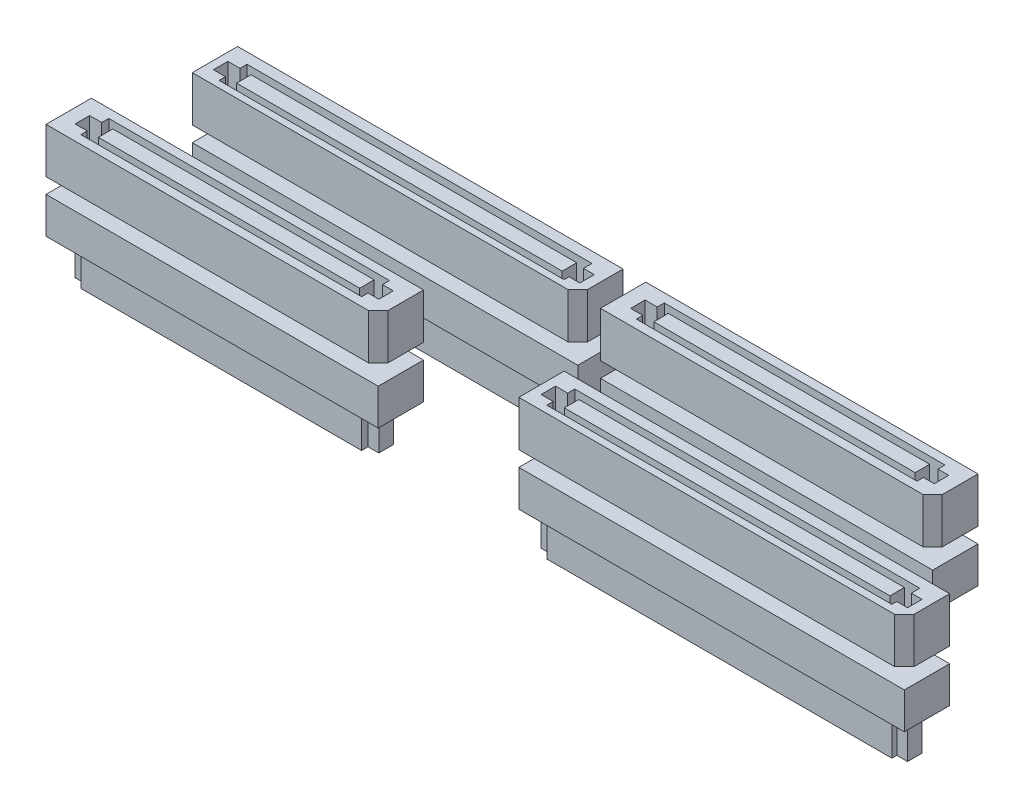
SolidWorks part; units mm, degrees
ref_plane "Front Plane" through (0, 0, 0) normal (0, 0, 1) x (1, 0, 0)
ref_plane "Top Plane" through (0, 0, 0) normal (0, 1, 0) x (1, 0, 0)
ref_plane "Right Plane" through (0, 0, 0) normal (1, 0, 0) x (0, 0, -1)
ref_plane "Plane1" through (0, -1.6866, 0) normal (0, 1, 0) x (1, 0, 0)
ref_plane "center-of-slot" through (0, -0.8433, 0) normal (0, 1, 0) x (1, 0, 0)
sketch "Sketch1" plane through (0, 0, 0) normal (0, 1, 0) x (1, 0, 0)
  line L0 (55.811, 9.5) -> (97.25, 9.5)
  line L1 (3.686, 9.5) -> (39.25, 9.5)
  line L2 (2.625, 8.439) -> (2.625, 4.5)
  line L3 (2.625, 4.5) -> (39.25, 4.5) construction
  line L4 (39.25, 9.5) -> (39.25, 4.5) construction
  line L5 (0, 0) -> (100, 0) construction
  line L6 (0, 0) -> (0, 75) construction
  line L7 (0, 75) -> (100, 75) construction
  line L8 (100, 0) -> (100, 75) construction
  line L9 (54.75, 8.439) -> (54.75, 4.5)
  line L10 (54.75, 4.5) -> (97.25, 4.5) construction
  line L11 (97.25, 9.5) -> (97.25, 4.5) construction
  line L12 (51.811, 22.5) -> (87.375, 22.5)
  line L13 (6.811, 22.5) -> (48.25, 22.5)
  line L14 (5.75, 21.439) -> (5.75, 17.5)
  line L15 (5.75, 17.5) -> (48.25, 17.5) construction
  line L16 (48.25, 22.5) -> (48.25, 17.5) construction
  line L17 (50.75, 21.439) -> (50.75, 17.5)
  line L18 (50.75, 17.5) -> (87.375, 17.5) construction
  line L19 (87.375, 22.5) -> (87.375, 17.5) construction
  line L20 (5.75, 21.439) -> (6.811, 22.5) construction
  line L21 (50.75, 21.439) -> (51.811, 22.5) construction
  line L22 (54.75, 8.439) -> (55.811, 9.5) construction
  line L23 (2.625, 8.439) -> (3.686, 9.5) construction
  line L24 (2.625, 4.5) -> (38.195, 4.5)
  line L25 (38.195, 4.5) -> (39.25, 5.555)
  line L26 (39.25, 5.555) -> (39.25, 9.5)
  line L27 (50.75, 17.5) -> (86.32, 17.5)
  line L28 (86.32, 17.5) -> (87.375, 18.555)
  line L29 (87.375, 18.555) -> (87.375, 22.5)
  line L30 (54.75, 4.5) -> (96.19, 4.5)
  line L31 (96.19, 4.5) -> (97.25, 5.56)
  line L32 (97.25, 5.56) -> (97.25, 9.5)
  line L33 (5.75, 17.5) -> (47.19, 17.5)
  line L34 (47.19, 17.5) -> (48.25, 18.56)
  line L35 (48.25, 18.56) -> (48.25, 22.5)
  line L36 (5.75, 21.439) -> (5.75, 22.5)
  line L37 (5.75, 22.5) -> (6.811, 22.5)
  line L38 (2.625, 8.439) -> (2.625, 9.5)
  line L39 (2.625, 9.5) -> (3.686, 9.5)
  line L40 (54.75, 8.439) -> (54.75, 9.5)
  line L41 (54.75, 9.5) -> (55.811, 9.5)
  line L42 (50.75, 21.439) -> (50.75, 22.5)
  line L43 (50.75, 22.5) -> (51.811, 22.5)
  point P0 (2.625, 9.5)
  point P9 (54.75, 9.5)
  point P13 (5.75, 22.5)
  point P17 (50.75, 22.5)
extrude "SV" add sketch "Sketch1" along normal blind 5
sketch "Sketch3" plane through (0, 5, 0) normal (0, 1, 0) x (1, 0, 0)
  line L0 (4.1893, 7.7457) -> (5.5243, 7.7457)
  line L1 (4.1893, 8.5242) -> (37.667, 8.5242) construction
  line L2 (4.1893, 8.5242) -> (4.1893, 5.4386) construction
  line L3 (4.1893, 5.4386) -> (37.667, 5.4386) construction
  line L4 (37.667, 8.5242) -> (37.667, 5.4386) construction
  line L5 (5.5243, 7.7457) -> (5.5243, 8.5242)
  line L6 (5.5243, 8.5242) -> (36.4757, 8.5242)
  line L7 (36.4757, 8.5242) -> (36.4757, 7.7457)
  line L8 (36.4757, 7.7457) -> (37.667, 7.7457)
  line L9 (37.667, 7.7457) -> (37.667, 6.1479)
  line L10 (37.667, 6.1479) -> (36.4757, 6.1479)
  line L11 (36.4757, 6.1479) -> (36.4757, 5.4386)
  line L12 (36.4757, 5.4386) -> (5.5243, 5.4386)
  line L13 (5.5243, 5.4386) -> (5.5243, 6.1479)
  line L14 (5.5243, 6.1479) -> (4.1893, 6.1479)
  line L15 (4.1893, 6.1479) -> (4.1893, 7.7457)
  line L16 (52.4211, 20.7536) -> (53.7561, 20.7536)
  line L17 (6.7471, 7.7457) -> (35.5588, 7.7457)
  line L18 (6.7471, 7.7457) -> (6.7471, 6.1479)
  line L19 (6.7471, 6.1479) -> (35.5588, 6.1479)
  line L20 (35.5588, 7.7457) -> (35.5588, 6.1479)
  line L21 (52.4211, 21.532) -> (85.8988, 21.532) construction
  line L22 (52.4211, 21.532) -> (52.4211, 18.4464) construction
  line L23 (52.4211, 18.4464) -> (85.8988, 18.4464) construction
  line L24 (85.8988, 21.532) -> (85.8988, 18.4464) construction
  line L25 (53.7561, 20.7536) -> (53.7561, 21.532)
  line L26 (53.7561, 21.532) -> (84.7075, 21.532)
  line L27 (84.7075, 21.532) -> (84.7075, 20.7536)
  line L28 (84.7075, 20.7536) -> (85.8988, 20.7536)
  line L29 (85.8988, 20.7536) -> (85.8988, 19.1558)
  line L30 (85.8988, 19.1558) -> (84.7075, 19.1558)
  line L31 (84.7075, 19.1558) -> (84.7075, 18.4464)
  line L32 (84.7075, 18.4464) -> (53.7561, 18.4464)
  line L33 (53.7561, 18.4464) -> (53.7561, 19.1558)
  line L34 (53.7561, 19.1558) -> (52.4211, 19.1558)
  line L35 (52.4211, 19.1558) -> (52.4211, 20.7536)
  line L36 (54.9789, 20.7536) -> (83.7906, 20.7536)
  line L37 (54.9789, 20.7536) -> (54.9789, 19.1558)
  line L38 (54.9789, 19.1558) -> (83.7906, 19.1558)
  line L39 (83.7906, 20.7536) -> (83.7906, 19.1558)
  line L40 (55.7059, 7.599) -> (57.0409, 7.599)
  line L41 (55.7059, 8.3775) -> (96.2696, 8.3775) construction
  line L42 (55.7059, 8.3775) -> (55.7059, 5.2919) construction
  line L43 (55.7059, 5.2919) -> (96.2696, 5.2919) construction
  line L44 (96.2696, 8.3775) -> (96.2696, 5.2919) construction
  line L45 (57.0409, 7.599) -> (57.0409, 8.3775)
  line L46 (57.0409, 8.3775) -> (95.0783, 8.3775)
  line L47 (95.0783, 8.3775) -> (95.0783, 7.4377)
  line L48 (95.0783, 7.4377) -> (96.2696, 7.4377)
  line L49 (96.2696, 7.4377) -> (96.2696, 5.8399)
  line L50 (96.2696, 5.8399) -> (95.0783, 5.8399)
  line L51 (95.0783, 5.8399) -> (95.0783, 5.2919)
  line L52 (95.0783, 5.2919) -> (57.0409, 5.2919)
  line L53 (57.0409, 5.2919) -> (57.0409, 6.0012)
  line L54 (57.0409, 6.0012) -> (55.7059, 6.0012)
  line L55 (55.7059, 6.0012) -> (55.7059, 7.599)
  line L56 (58.2637, 7.599) -> (94.1615, 7.599)
  line L57 (58.2637, 7.599) -> (58.2637, 6.0012)
  line L58 (58.2637, 6.0012) -> (94.1615, 6.0012)
  line L59 (94.1615, 7.599) -> (94.1615, 6.0012)
  line L60 (6.6366, 20.5397) -> (7.9716, 20.5397)
  line L61 (6.6366, 21.3182) -> (47.2003, 21.3182) construction
  line L62 (6.6366, 21.3182) -> (6.6366, 18.2325) construction
  line L63 (6.6366, 18.2325) -> (47.2003, 18.2325) construction
  line L64 (47.2003, 21.3182) -> (47.2003, 18.2325) construction
  line L65 (7.9716, 20.5397) -> (7.9716, 21.3182)
  line L66 (7.9716, 21.3182) -> (46.009, 21.3182)
  line L67 (46.009, 21.3182) -> (46.009, 20.3784)
  line L68 (46.009, 20.3784) -> (47.2003, 20.3784)
  line L69 (47.2003, 20.3784) -> (47.2003, 18.7806)
  line L70 (47.2003, 18.7806) -> (46.009, 18.7806)
  line L71 (46.009, 18.7806) -> (46.009, 18.2325)
  line L72 (46.009, 18.2325) -> (7.9716, 18.2325)
  line L73 (7.9716, 18.2325) -> (7.9716, 18.9419)
  line L74 (7.9716, 18.9419) -> (6.6366, 18.9419)
  line L75 (6.6366, 18.9419) -> (6.6366, 20.5397)
  line L76 (9.1944, 20.5397) -> (45.0922, 20.5397)
  line L77 (9.1944, 20.5397) -> (9.1944, 18.9419)
  line L78 (9.1944, 18.9419) -> (45.0922, 18.9419)
  line L79 (45.0922, 20.5397) -> (45.0922, 18.9419)
extrude "Cut-Extrude1" cut sketch "Sketch3" against normal blind 4
sketch "Sketch6" plane through (0, -1.6866, 0) normal (0, 1, 0) x (1, 0, 0)
  line L0 (2.625, 4.5) -> (2.625, 9.5) construction
  line L1 (5.75, 22.5) -> (48.25, 22.5) construction
  line L2 (5.75, 22.5) -> (5.75, 17.5) construction
  line L3 (5.75, 17.5) -> (48.25, 17.5) construction
  line L4 (48.25, 22.5) -> (48.25, 17.5) construction
  line L5 (50.75, 22.5) -> (87.375, 22.5) construction
  line L6 (50.75, 22.5) -> (50.75, 17.5) construction
  line L7 (50.75, 17.5) -> (87.375, 17.5) construction
  line L8 (87.375, 22.5) -> (87.375, 17.5) construction
  line L9 (97.25, 9.5) -> (54.75, 9.5) construction
  line L10 (97.25, 9.5) -> (97.25, 4.5) construction
  line L11 (97.25, 4.5) -> (54.75, 4.5) construction
  line L12 (54.75, 9.5) -> (54.75, 4.5) construction
  line L13 (39.25, 9.5) -> (2.625, 9.5) construction
  line L14 (39.25, 9.5) -> (39.25, 4.5) construction
  line L15 (39.25, 4.5) -> (2.625, 4.5) construction
  line L16 (2.625, 9.5) -> (2.625, 4.5) construction
  line L17 (2.625, 4.5) -> (38.195, 4.5)
  line L18 (2.625, 9.5) -> (39.25, 9.5) construction
  line L19 (48.25, 18.5619) -> (47.1881, 17.5) construction
  line L20 (39.25, 5.555) -> (39.25, 9.5)
  line L21 (48.25, 18.5619) -> (48.25, 22.5)
  line L22 (47.1881, 17.5) -> (5.75, 17.5)
  line L23 (39.25, 5.555) -> (38.195, 4.5) construction
  line L24 (54.75, 4.5) -> (96.19, 4.5)
  line L25 (96.19, 4.5) -> (97.25, 5.56) construction
  line L26 (97.25, 5.56) -> (97.25, 9.5)
  line L27 (50.75, 17.5) -> (86.32, 17.5)
  line L28 (86.32, 17.5) -> (87.375, 18.555) construction
  line L29 (87.375, 18.555) -> (87.375, 22.5)
  line L30 (2.625, 4.5) -> (2.625, 8.44)
  line L31 (2.625, 8.44) -> (3.685, 9.5)
  line L32 (3.685, 9.5) -> (39.25, 9.5)
  line L33 (5.75, 17.5) -> (5.75, 21.44)
  line L34 (5.75, 21.44) -> (6.81, 22.5)
  line L35 (6.81, 22.5) -> (48.25, 22.5)
  line L36 (54.75, 4.5) -> (54.75, 8.44)
  line L37 (54.75, 8.44) -> (55.81, 9.5)
  line L38 (55.81, 9.5) -> (97.25, 9.5)
  line L39 (87.375, 22.5) -> (51.805, 22.5)
  line L40 (51.805, 22.5) -> (50.75, 21.445)
  line L41 (50.75, 21.445) -> (50.75, 17.5)
  line L42 (47.1881, 17.5) -> (48.25, 17.5)
  line L43 (48.25, 17.5) -> (48.25, 18.5619)
  line L44 (38.195, 4.5) -> (39.25, 4.5)
  line L45 (39.25, 4.5) -> (39.25, 5.555)
  line L46 (96.19, 4.5) -> (97.25, 4.5)
  line L47 (97.25, 4.5) -> (97.25, 5.56)
  line L48 (86.32, 17.5) -> (87.375, 17.5)
  line L49 (87.375, 17.5) -> (87.375, 18.555)
  point P0 (5.75, 22.5)
  point P6 (50.75, 22.5)
  point P15 (54.75, 9.5)
extrude "SV4(a)" add sketch "Sketch6" against normal blind 4 separate body
sketch "Sketch7" plane through (0, -5.6866, 0) normal (0, -1, 0) x (1, 0, 0)
  line L0 (7.9716, -21.3182) -> (7.9716, -20.5397)
  line L1 (7.9716, -20.5397) -> (6.6366, -20.5397)
  line L2 (6.6366, -20.5397) -> (6.6366, -18.9419)
  line L3 (6.6366, -18.9419) -> (7.9716, -18.9419)
  line L4 (7.9716, -18.9419) -> (7.9716, -18.2325)
  line L6 (7.9716, -18.2325) -> (46.009, -18.2325)
  line L7 (46.009, -18.2325) -> (46.009, -18.7806)
  line L8 (46.009, -18.7806) -> (47.2003, -18.7806)
  line L9 (47.2003, -18.7806) -> (47.2003, -20.3784)
  line L10 (47.2003, -20.3784) -> (46.009, -20.3784)
  line L11 (46.009, -20.3784) -> (46.009, -21.3182)
  line L12 (46.009, -21.3182) -> (7.9716, -21.3182)
  line L13 (53.7561, -21.532) -> (84.7075, -21.532)
  line L14 (9.1944, -20.5397) -> (45.0922, -20.5397)
  line L15 (9.1944, -20.5397) -> (9.1944, -18.9419)
  line L16 (9.1944, -18.9419) -> (45.0922, -18.9419)
  line L17 (45.0922, -20.5397) -> (45.0922, -18.9419)
  line L18 (54.9789, -20.7536) -> (83.7906, -20.7536)
  line L19 (54.9789, -20.7536) -> (54.9789, -19.1558)
  line L20 (54.9789, -19.1558) -> (83.7906, -19.1558)
  line L21 (83.7906, -20.7536) -> (83.7906, -19.1558)
  line L22 (94.1615, -7.599) -> (58.2637, -7.599)
  line L23 (94.1615, -7.599) -> (94.1615, -6.0012)
  line L24 (94.1615, -6.0012) -> (58.2637, -6.0012)
  line L25 (58.2637, -7.599) -> (58.2637, -6.0012)
  line L26 (35.5588, -7.7457) -> (6.7471, -7.7457)
  line L27 (35.5588, -7.7457) -> (35.5588, -6.1479)
  line L28 (35.5588, -6.1479) -> (6.7471, -6.1479)
  line L29 (6.7471, -7.7457) -> (6.7471, -6.1479)
  line L30 (84.7075, -21.532) -> (84.7075, -20.7536)
  line L31 (84.7075, -20.7536) -> (85.8988, -20.7536)
  line L32 (85.8988, -20.7536) -> (85.8988, -19.1558)
  line L33 (85.8988, -19.1558) -> (84.7075, -19.1558)
  line L34 (84.7075, -19.1558) -> (84.7075, -18.4464)
  line L35 (84.7075, -18.4464) -> (53.7561, -18.4464)
  line L36 (53.7561, -18.4464) -> (53.7561, -19.1558)
  line L37 (53.7561, -19.1558) -> (52.4211, -19.1558)
  line L38 (52.4211, -19.1558) -> (52.4211, -20.7536)
  line L39 (52.4211, -20.7536) -> (53.7561, -20.7536)
  line L40 (53.7561, -20.7536) -> (53.7561, -21.532)
  line L41 (57.0409, -8.3775) -> (57.0409, -7.599)
  line L42 (57.0409, -7.599) -> (55.7059, -7.599)
  line L43 (55.7059, -7.599) -> (55.7059, -6.0012)
  line L44 (55.7059, -6.0012) -> (57.0409, -6.0012)
  line L45 (57.0409, -6.0012) -> (57.0409, -5.2919)
  line L46 (57.0409, -5.2919) -> (95.0783, -5.2919)
  line L47 (95.0783, -5.2919) -> (95.0783, -5.8399)
  line L48 (95.0783, -5.8399) -> (96.2696, -5.8399)
  line L49 (96.2696, -5.8399) -> (96.2696, -7.4377)
  line L50 (96.2696, -7.4377) -> (95.0783, -7.4377)
  line L51 (95.0783, -7.4377) -> (95.0783, -8.3775)
  line L52 (95.0783, -8.3775) -> (57.0409, -8.3775)
  line L53 (4.1893, -6.1479) -> (5.5243, -6.1479)
  line L54 (5.5243, -6.1479) -> (5.5243, -5.4386)
  line L55 (5.5243, -5.4386) -> (36.4757, -5.4386)
  line L56 (36.4757, -5.4386) -> (36.4757, -6.1479)
  line L57 (36.4757, -6.1479) -> (37.667, -6.1479)
  line L58 (37.667, -6.1479) -> (37.667, -7.7457)
  line L59 (37.667, -7.7457) -> (36.4757, -7.7457)
  line L60 (36.4757, -7.7457) -> (36.4757, -8.5242)
  line L61 (36.4757, -8.5242) -> (5.5243, -8.5242)
  line L62 (5.5243, -8.5242) -> (5.5243, -7.7457)
  line L63 (5.5243, -7.7457) -> (4.1893, -7.7457)
  line L64 (4.1893, -7.7457) -> (4.1893, -6.1479)
extrude "SV4(b)" add sketch "Sketch7" along normal blind 4
